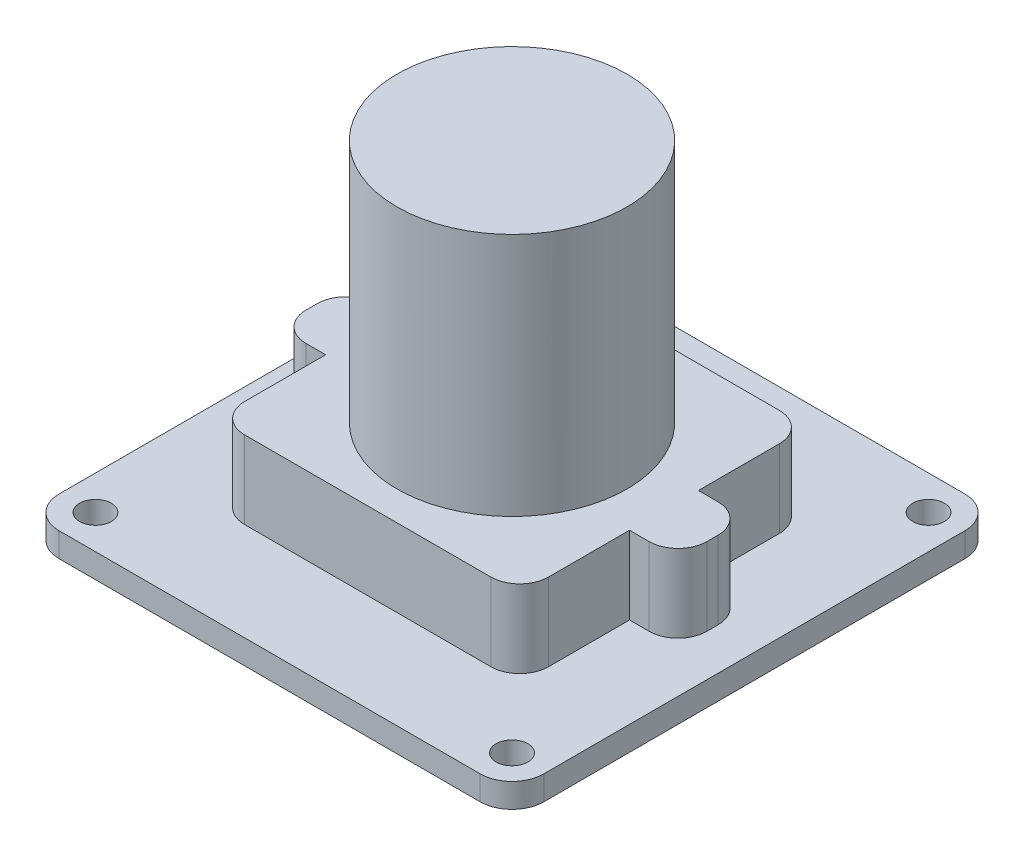
SolidWorks part; units mm, degrees
ref_plane "Front Plane" through (0, 0, 0) normal (0, 0, 1) x (1, 0, 0)
ref_plane "Top Plane" through (0, 0, 0) normal (0, 1, 0) x (1, 0, 0)
ref_plane "Right Plane" through (0, 0, 0) normal (1, 0, 0) x (0, 0, -1)
sketch "Sketch1" plane through (0, 0, 0) normal (0, 1, 0) x (1, 0, 0)
  line L0 (0, 0) -> (0, 51030.1207) construction
  line L1 (0, 0) -> (-51030.1207, 0) construction
  line L3 (-16, 16) -> (16, 16)
  line L4 (-16, 16) -> (-16, -16)
  line L5 (-16, -16) -> (16, -16)
  line L6 (16, 16) -> (16, -16)
  circle A0 centre (13.75, 13.75) radius 1.0478
  circle A1 centre (-13.75, 13.75) radius 1.0478
  circle A2 centre (-13.75, -13.75) radius 1.0478
  circle A3 centre (13.75, -13.75) radius 1.0478
  point P9 (0, 16)
  point P10 (-16, 0)
  dimension "D3" = 2.0955
  dimension "D4" = 2.0955
  dimension "D5" = 2.0955
  dimension "D6" = 2.0955
  dimension "D1" = 32
  dimension "D2" = 32
  dimension "D7" = 13.75
  dimension "D8" = 13.75
  dimension "D9" = 13.75
  dimension "D10" = 13.75
  dimension "D11" = 13.75
  dimension "D12" = 13.75
  dimension "D13" = 13.75
  dimension "D14" = 13.75
extrude "Boss-Extrude1" add sketch "Sketch1" along normal blind 1.6002
sketch "Sketch2" plane through (0, 1.6002, 0) normal (0, 1, 0) x (1, 0, 0)
  line L0 (0, 0) -> (-50000, 0) construction
  line L1 (-10.033, 9.525) -> (10.033, 9.525)
  line L2 (-10.033, 9.525) -> (-10.033, 2.2733)
  line L3 (-10.033, -9.525) -> (10.033, -9.525)
  line L4 (10.033, 9.525) -> (10.033, 2.2733)
  line L5 (-10.033, 2.2733) -> (-13.2334, 2.2733)
  line L6 (-13.2334, 2.2733) -> (-13.2334, -2.2733)
  line L7 (-13.2334, -2.2733) -> (-10.033, -2.2733)
  line L8 (10.033, 2.2733) -> (13.2334, 2.2733)
  line L9 (13.2334, 2.2733) -> (13.2334, -2.2733)
  line L10 (13.2334, -2.2733) -> (10.033, -2.2733)
  line L11 (-10.033, -2.2733) -> (-10.033, -9.525)
  line L12 (10.033, -2.2733) -> (10.033, -9.525)
  point P4 (0, 9.525)
  point P15 (13.2334, 0)
  point P18 (-13.2334, 0)
  dimension "D1" = 20.066
  dimension "D2" = 19.05
  dimension "D3" = 3.2004
  dimension "D4" = 4.5466
  dimension "D5" = 3.2004
  dimension "D6" = 9.525
extrude "Boss-Extrude2" add sketch "Sketch2" along normal blind 5.1308
fillet "Fillet1" radius 2.1 4 edges at (-16, 0.8001, -16) (16, 0.8001, -16) (16, 0.8001, 16) (-16, 0.8001, 16)
fillet "Fillet2" radius 1.905 8 edges at (-10.033, 4.1656, -9.525) (10.033, 4.1656, -9.525) (13.2334, 4.1656, -2.2733) (13.2334, 4.1656, 2.2733) (10.033, 4.1656, 9.525) (-10.033, 4.1656, 9.525) (-13.2334, 4.1656, 2.2733) (-13.2334, 4.1656, -2.2733)
sketch "Sketch3" plane through (0, 6.731, 0) normal (0, 1, 0) x (1, 0, 0)
  circle A0 centre (0, 0) radius 7.5946
  dimension "D1" = 15.1892
extrude "Boss-Extrude3" add sketch "Sketch3" along normal blind 16.129
